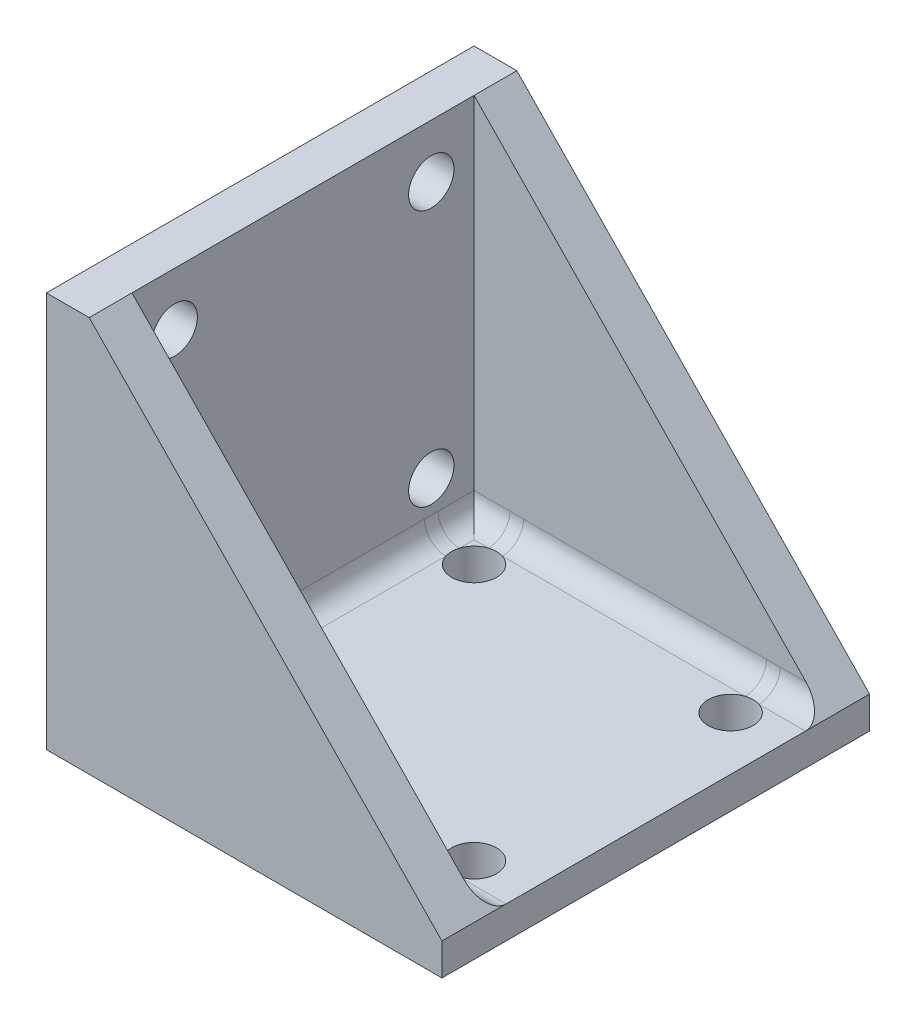
SolidWorks part; units mm, degrees
ref_plane "Front Plane" through (0, 0, 0) normal (0, 0, 1) x (1, 0, 0)
ref_plane "Top Plane" through (0, 0, 0) normal (0, 1, 0) x (1, 0, 0)
ref_plane "Right Plane" through (0, 0, 0) normal (1, 0, 0) x (0, 0, -1)
sketch "sss" plane through (0, 0, 0) normal (0, 1, 0) x (1, 0, 0)
  line L0 (-23, 0) -> (17, 0) construction
  line L1 (-20, -20) -> (17, -20)
  line L3 (-20, 20) -> (17, 20)
  line L4 (17, -20) -> (17, 20)
  line L5 (-19.6365, -23.1018) -> (17, 20) construction
  line L6 (-19.6365, 23.1018) -> (17, -20) construction
  line L7 (-1.5, 20) -> (-1.5, -20) construction
  line L8 (-20, 20) -> (-20, -20)
  circle A0 centre (-12, 12) radius 2.1
  circle A5 centre (12, 12) radius 2.1
  circle A6 centre (12, -12) radius 2.1
  circle A7 centre (-12, -12) radius 2.1
  point P0 (0, 0)
  dimension "D3" = 4.2
  dimension "D4" = 8
  dimension "D5" = 5
  dimension "D2" = 8
  dimension "D6" = 8
  dimension "D1" = 24
extrude "Boss-Extrude2" add sketch "sss" along normal blind 3
sketch "Sketch1" plane through (-20, 0, 0) normal (-1, 0, 0) x (0, 0, 1)
  line L0 (-20, 37) -> (20, 3) construction
  line L1 (-20, 0) -> (20, 0)
  line L2 (-20, 0) -> (-20, 37)
  line L3 (-20, 37) -> (20, 37)
  line L4 (20, 0) -> (20, 37)
  line L5 (20, 37) -> (-20, 3) construction
  line L6 (-20, 20) -> (20, 20) construction
  line L7 (0, 37) -> (0, 0) construction
  circle A1 centre (-12, 32) radius 2.125
  circle A2 centre (12, 32) radius 2.125
  circle A3 centre (12, 8) radius 2.125
  circle A4 centre (-12, 8) radius 2.125
  dimension "D2" = 4.25
  dimension "D1" = 12
  dimension "D3" = 5
  dimension "D4" = 8
  dimension "D5" = 8
extrude "Boss-Extrude3" add sketch "Sketch1" against normal blind 4
sketch "Sketch2" plane through (0, 0, 20) normal (0, 0, 1) x (1, 0, 0)
  line L0 (-20, 37) -> (-20, 0)
  line L1 (-20, 0) -> (17, 0) construction
  line L2 (-20, 37) -> (-20, 0) construction
  line L3 (-20, 0) -> (17, 0)
  line L4 (17, 0) -> (17, 3)
  line L5 (17, 3) -> (-16, 37)
  line L6 (-16, 37) -> (-20, 37)
extrude "Boss-Extrude4" add sketch "Sketch2" against normal blind 4
ref_plane "Plane1" through (0, 0, 0) normal (0, 0, 1) x (1, 0, 0)
mirror "Mirror1" about plane through (0, 0, 0) normal (0, 0, 1) of "Boss-Extrude4"
fillet "Fillet1" radius 2 3 edges at (0.5, 3, -16) (0.5, 3, 16) (-16, 3, 0)
equation "\"m4\"= 4.2"
equation "\"D3@sss\"=\"m4\""
